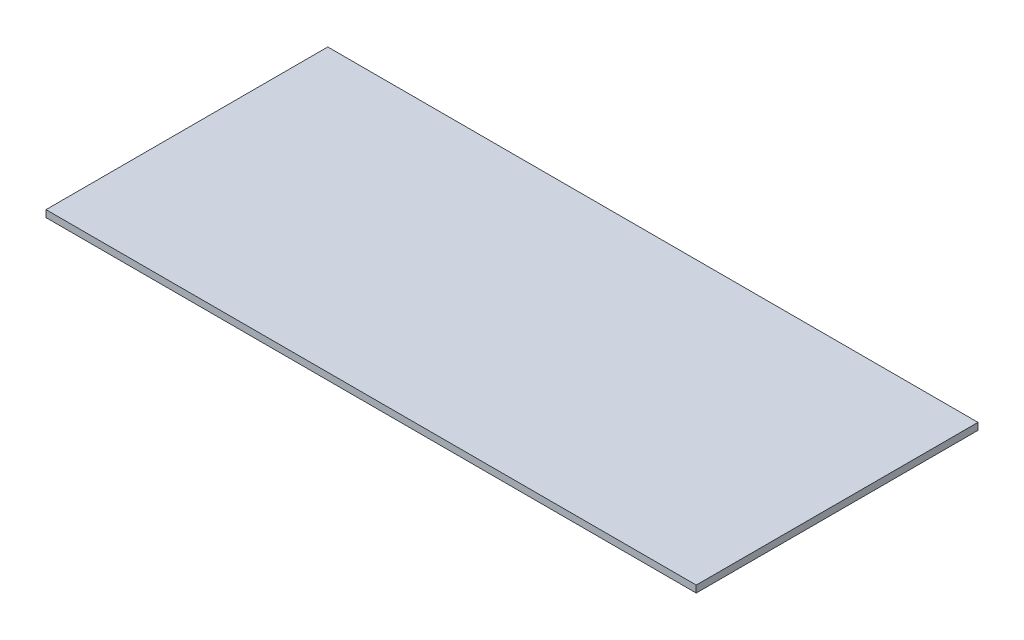
SolidWorks part; units mm, degrees
ref_plane "Front Plane" through (0, 0, 0) normal (0, 0, 1) x (1, 0, 0)
ref_plane "Top Plane" through (0, 0, 0) normal (0, 1, 0) x (1, 0, 0)
ref_plane "Right Plane" through (0, 0, 0) normal (1, 0, 0) x (0, 0, -1)
sketch "Sketch1" plane through (0, 0, 0) normal (0, 1, 0) x (1, 0, 0)
  line L1 (-750, -325) -> (750, -325)
  line L2 (-750, -325) -> (-750, 325)
  line L3 (-750, 325) -> (750, 325)
  line L4 (750, -325) -> (750, 325)
  line L5 (-750, -325) -> (750, 325) construction
  line L6 (-750, 325) -> (750, -325) construction
  point P0 (0, 0)
  dimension "D1" = 650
  dimension "D2" = 1500
extrude "Boss-Extrude1" add sketch "Sketch1" along normal blind 16 contours L2 L3 L4 L1
